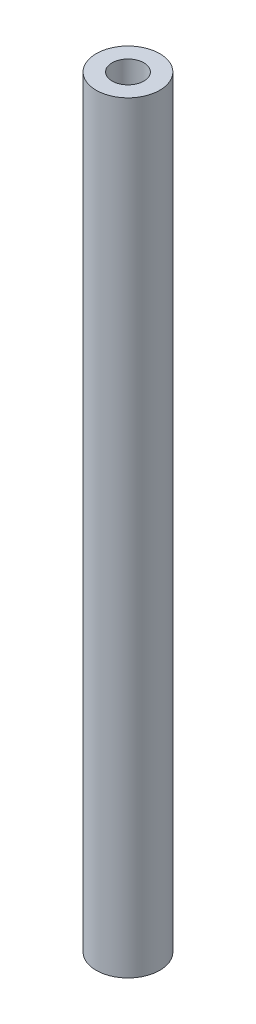
SolidWorks part; units mm, degrees
ref_plane "Alzado" through (0, 0, 0) normal (0, 0, 1) x (1, 0, 0)
ref_plane "Planta" through (0, 0, 0) normal (0, 1, 0) x (1, 0, 0)
ref_plane "Vista lateral" through (0, 0, 0) normal (1, 0, 0) x (0, 0, -1)
sketch "Croquis base" plane through (0, 0, 0) normal (0, 1, 0) x (1, 0, 0)
  circle A0 centre (0, 0) radius 2.5
  dimension "D1" = 5
extrude "Saliente-Extruir1" add sketch "Croquis base" along normal blind 60
sketch "Croquis barreno" plane through (0, 60, 0) normal (0, 1, 0) x (1, 0, 0)
  circle A0 centre (0, 0) radius 1.25
  dimension "D1" = 2.5
extrude "Cortar-Extruir1" cut sketch "Croquis barreno" against normal through all
